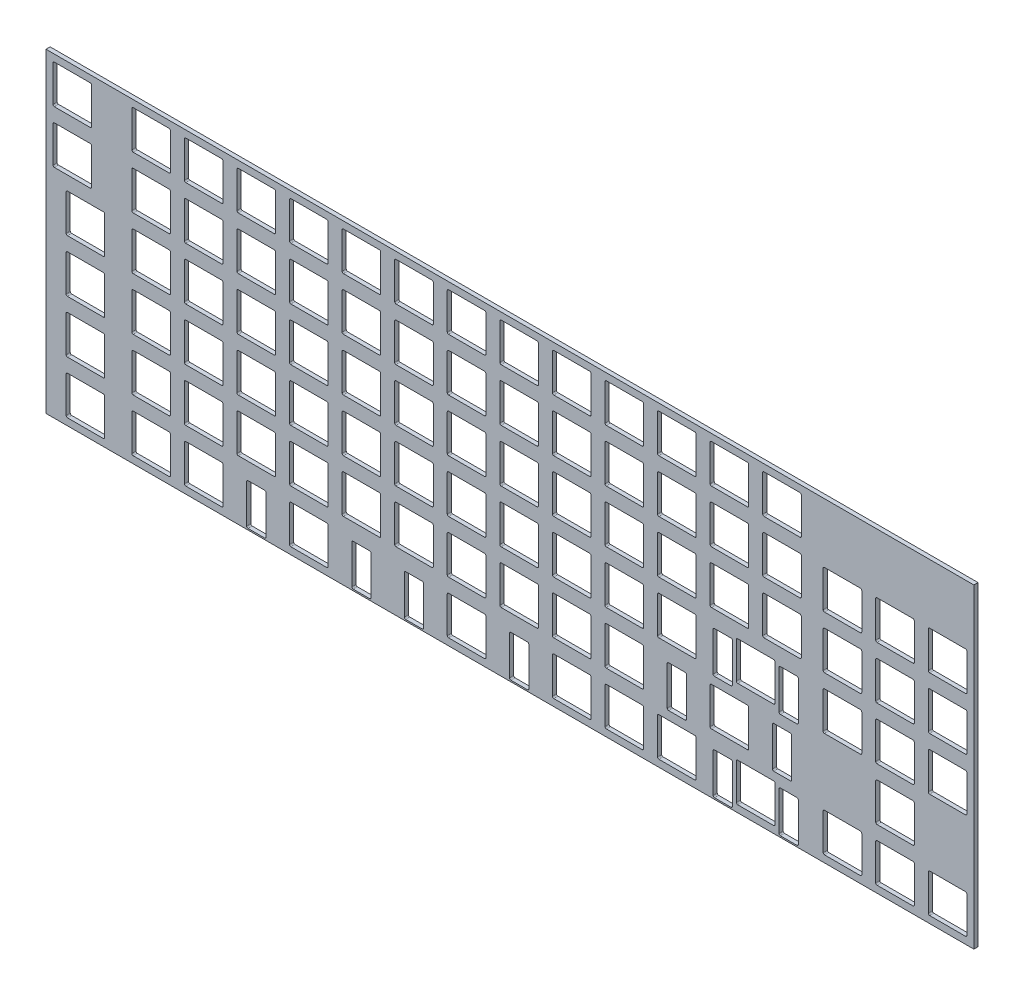
SolidWorks part; units mm, degrees
ref_plane "Front Plane" through (0, 0, 0) normal (0, 0, 1) x (1, 0, 0)
ref_plane "Top Plane" through (0, 0, 0) normal (0, 1, 0) x (1, 0, 0)
ref_plane "Right Plane" through (0, 0, 0) normal (1, 0, 0) x (0, 0, -1)
sketch "Model" plane through (0, 0, 0) normal (0, 0, 1) x (1, 0, 0)
  line L0 (3.025, -2.525) -> (16.025, -2.525)
  line L1 (3.025, -16.525) -> (16.025, -16.525)
  line L2 (2.525, -3.025) -> (2.525, -16.025)
  line L3 (16.525, -3.025) -> (16.525, -16.025)
  line L4 (31.6, -2.525) -> (44.6, -2.525)
  line L5 (31.6, -16.525) -> (44.6, -16.525)
  line L6 (31.1, -3.025) -> (31.1, -16.025)
  line L7 (45.1, -3.025) -> (45.1, -16.025)
  line L8 (50.65, -2.525) -> (63.65, -2.525)
  line L9 (50.65, -16.525) -> (63.65, -16.525)
  line L10 (50.15, -3.025) -> (50.15, -16.025)
  line L11 (64.15, -3.025) -> (64.15, -16.025)
  line L12 (69.7, -2.525) -> (82.7, -2.525)
  line L13 (69.7, -16.525) -> (82.7, -16.525)
  line L14 (69.2, -3.025) -> (69.2, -16.025)
  line L15 (83.2, -3.025) -> (83.2, -16.025)
  line L16 (88.75, -2.525) -> (101.75, -2.525)
  line L17 (88.75, -16.525) -> (101.75, -16.525)
  line L18 (88.25, -3.025) -> (88.25, -16.025)
  line L19 (102.25, -3.025) -> (102.25, -16.025)
  line L20 (107.8, -2.525) -> (120.8, -2.525)
  line L21 (107.8, -16.525) -> (120.8, -16.525)
  line L22 (107.3, -3.025) -> (107.3, -16.025)
  line L23 (121.3, -3.025) -> (121.3, -16.025)
  line L24 (126.85, -2.525) -> (139.85, -2.525)
  line L25 (126.85, -16.525) -> (139.85, -16.525)
  line L26 (126.35, -3.025) -> (126.35, -16.025)
  line L27 (140.35, -3.025) -> (140.35, -16.025)
  line L28 (145.9, -2.525) -> (158.9, -2.525)
  line L29 (145.9, -16.525) -> (158.9, -16.525)
  line L30 (145.4, -3.025) -> (145.4, -16.025)
  line L31 (159.4, -3.025) -> (159.4, -16.025)
  line L32 (164.95, -2.525) -> (177.95, -2.525)
  line L33 (164.95, -16.525) -> (177.95, -16.525)
  line L34 (164.45, -3.025) -> (164.45, -16.025)
  line L35 (178.45, -3.025) -> (178.45, -16.025)
  line L36 (184, -2.525) -> (197, -2.525)
  line L37 (184, -16.525) -> (197, -16.525)
  line L38 (183.5, -3.025) -> (183.5, -16.025)
  line L39 (197.5, -3.025) -> (197.5, -16.025)
  line L40 (203.05, -2.525) -> (216.05, -2.525)
  line L41 (203.05, -16.525) -> (216.05, -16.525)
  line L42 (202.55, -3.025) -> (202.55, -16.025)
  line L43 (216.55, -3.025) -> (216.55, -16.025)
  line L44 (222.1, -2.525) -> (235.1, -2.525)
  line L45 (222.1, -16.525) -> (235.1, -16.525)
  line L46 (221.6, -3.025) -> (221.6, -16.025)
  line L47 (235.6, -3.025) -> (235.6, -16.025)
  line L48 (241.15, -2.525) -> (254.15, -2.525)
  line L49 (241.15, -16.525) -> (254.15, -16.525)
  line L50 (240.65, -3.025) -> (240.65, -16.025)
  line L51 (254.65, -3.025) -> (254.65, -16.025)
  line L52 (260.2, -2.525) -> (273.2, -2.525)
  line L53 (260.2, -16.525) -> (273.2, -16.525)
  line L54 (259.7, -3.025) -> (259.7, -16.025)
  line L55 (273.7, -3.025) -> (273.7, -16.025)
  line L56 (3.025, -21.575) -> (16.025, -21.575)
  line L57 (3.025, -35.575) -> (16.025, -35.575)
  line L58 (2.525, -22.075) -> (2.525, -35.075)
  line L59 (16.525, -22.075) -> (16.525, -35.075)
  line L60 (31.6, -21.575) -> (44.6, -21.575)
  line L61 (31.6, -35.575) -> (44.6, -35.575)
  line L62 (31.1, -22.075) -> (31.1, -35.075)
  line L63 (45.1, -22.075) -> (45.1, -35.075)
  line L64 (50.65, -21.575) -> (63.65, -21.575)
  line L65 (50.65, -35.575) -> (63.65, -35.575)
  line L66 (50.15, -22.075) -> (50.15, -35.075)
  line L67 (64.15, -22.075) -> (64.15, -35.075)
  line L68 (69.7, -21.575) -> (82.7, -21.575)
  line L69 (69.7, -35.575) -> (82.7, -35.575)
  line L70 (69.2, -22.075) -> (69.2, -35.075)
  line L71 (83.2, -22.075) -> (83.2, -35.075)
  line L72 (88.75, -21.575) -> (101.75, -21.575)
  line L73 (88.75, -35.575) -> (101.75, -35.575)
  line L74 (88.25, -22.075) -> (88.25, -35.075)
  line L75 (102.25, -22.075) -> (102.25, -35.075)
  line L76 (107.8, -21.575) -> (120.8, -21.575)
  line L77 (107.8, -35.575) -> (120.8, -35.575)
  line L78 (107.3, -22.075) -> (107.3, -35.075)
  line L79 (121.3, -22.075) -> (121.3, -35.075)
  line L80 (126.85, -21.575) -> (139.85, -21.575)
  line L81 (126.85, -35.575) -> (139.85, -35.575)
  line L82 (126.35, -22.075) -> (126.35, -35.075)
  line L83 (140.35, -22.075) -> (140.35, -35.075)
  line L84 (145.9, -21.575) -> (158.9, -21.575)
  line L85 (145.9, -35.575) -> (158.9, -35.575)
  line L86 (145.4, -22.075) -> (145.4, -35.075)
  line L87 (159.4, -22.075) -> (159.4, -35.075)
  line L88 (164.95, -21.575) -> (177.95, -21.575)
  line L89 (164.95, -35.575) -> (177.95, -35.575)
  line L90 (164.45, -22.075) -> (164.45, -35.075)
  line L91 (178.45, -22.075) -> (178.45, -35.075)
  line L92 (184, -21.575) -> (197, -21.575)
  line L93 (184, -35.575) -> (197, -35.575)
  line L94 (183.5, -22.075) -> (183.5, -35.075)
  line L95 (197.5, -22.075) -> (197.5, -35.075)
  line L96 (203.05, -21.575) -> (216.05, -21.575)
  line L97 (203.05, -35.575) -> (216.05, -35.575)
  line L98 (202.55, -22.075) -> (202.55, -35.075)
  line L99 (216.55, -22.075) -> (216.55, -35.075)
  line L100 (222.1, -21.575) -> (235.1, -21.575)
  line L101 (222.1, -35.575) -> (235.1, -35.575)
  line L102 (221.6, -22.075) -> (221.6, -35.075)
  line L103 (235.6, -22.075) -> (235.6, -35.075)
  line L104 (241.15, -21.575) -> (254.15, -21.575)
  line L105 (241.15, -35.575) -> (254.15, -35.575)
  line L106 (240.65, -22.075) -> (240.65, -35.075)
  line L107 (254.65, -22.075) -> (254.65, -35.075)
  line L108 (260.2, -21.575) -> (273.2, -21.575)
  line L109 (260.2, -35.575) -> (273.2, -35.575)
  line L110 (259.7, -22.075) -> (259.7, -35.075)
  line L111 (273.7, -22.075) -> (273.7, -35.075)
  line L112 (282.1075, -21.575) -> (295.1075, -21.575)
  line L113 (282.1075, -35.575) -> (295.1075, -35.575)
  line L114 (281.6075, -22.075) -> (281.6075, -35.075)
  line L115 (295.6075, -22.075) -> (295.6075, -35.075)
  line L116 (301.1575, -21.575) -> (314.1575, -21.575)
  line L117 (301.1575, -35.575) -> (314.1575, -35.575)
  line L118 (300.6575, -22.075) -> (300.6575, -35.075)
  line L119 (314.6575, -22.075) -> (314.6575, -35.075)
  line L120 (320.2075, -21.575) -> (333.2075, -21.575)
  line L121 (320.2075, -35.575) -> (333.2075, -35.575)
  line L122 (319.7075, -22.075) -> (319.7075, -35.075)
  line L123 (333.7075, -22.075) -> (333.7075, -35.075)
  line L124 (7.7875, -40.625) -> (20.7875, -40.625)
  line L125 (7.7875, -54.625) -> (20.7875, -54.625)
  line L126 (7.2875, -41.125) -> (7.2875, -54.125)
  line L127 (21.2875, -41.125) -> (21.2875, -54.125)
  line L128 (31.6, -40.625) -> (44.6, -40.625)
  line L129 (31.6, -54.625) -> (44.6, -54.625)
  line L130 (31.1, -41.125) -> (31.1, -54.125)
  line L131 (45.1, -41.125) -> (45.1, -54.125)
  line L132 (50.65, -40.625) -> (63.65, -40.625)
  line L133 (50.65, -54.625) -> (63.65, -54.625)
  line L134 (50.15, -41.125) -> (50.15, -54.125)
  line L135 (64.15, -41.125) -> (64.15, -54.125)
  line L136 (69.7, -40.625) -> (82.7, -40.625)
  line L137 (69.7, -54.625) -> (82.7, -54.625)
  line L138 (69.2, -41.125) -> (69.2, -54.125)
  line L139 (83.2, -41.125) -> (83.2, -54.125)
  line L140 (88.75, -40.625) -> (101.75, -40.625)
  line L141 (88.75, -54.625) -> (101.75, -54.625)
  line L142 (88.25, -41.125) -> (88.25, -54.125)
  line L143 (102.25, -41.125) -> (102.25, -54.125)
  line L144 (107.8, -40.625) -> (120.8, -40.625)
  line L145 (107.8, -54.625) -> (120.8, -54.625)
  line L146 (107.3, -41.125) -> (107.3, -54.125)
  line L147 (121.3, -41.125) -> (121.3, -54.125)
  line L148 (126.85, -40.625) -> (139.85, -40.625)
  line L149 (126.85, -54.625) -> (139.85, -54.625)
  line L150 (126.35, -41.125) -> (126.35, -54.125)
  line L151 (140.35, -41.125) -> (140.35, -54.125)
  line L152 (145.9, -40.625) -> (158.9, -40.625)
  line L153 (145.9, -54.625) -> (158.9, -54.625)
  line L154 (145.4, -41.125) -> (145.4, -54.125)
  line L155 (159.4, -41.125) -> (159.4, -54.125)
  line L156 (164.95, -40.625) -> (177.95, -40.625)
  line L157 (164.95, -54.625) -> (177.95, -54.625)
  line L158 (164.45, -41.125) -> (164.45, -54.125)
  line L159 (178.45, -41.125) -> (178.45, -54.125)
  line L160 (184, -40.625) -> (197, -40.625)
  line L161 (184, -54.625) -> (197, -54.625)
  line L162 (183.5, -41.125) -> (183.5, -54.125)
  line L163 (197.5, -41.125) -> (197.5, -54.125)
  line L164 (203.05, -40.625) -> (216.05, -40.625)
  line L165 (203.05, -54.625) -> (216.05, -54.625)
  line L166 (202.55, -41.125) -> (202.55, -54.125)
  line L167 (216.55, -41.125) -> (216.55, -54.125)
  line L168 (222.1, -40.625) -> (235.1, -40.625)
  line L169 (222.1, -54.625) -> (235.1, -54.625)
  line L170 (221.6, -41.125) -> (221.6, -54.125)
  line L171 (235.6, -41.125) -> (235.6, -54.125)
  line L172 (241.15, -40.625) -> (254.15, -40.625)
  line L173 (241.15, -54.625) -> (254.15, -54.625)
  line L174 (240.65, -41.125) -> (240.65, -54.125)
  line L175 (254.65, -41.125) -> (254.65, -54.125)
  line L176 (260.2, -40.625) -> (273.2, -40.625)
  line L177 (260.2, -54.625) -> (273.2, -54.625)
  line L178 (259.7, -41.125) -> (259.7, -54.125)
  line L179 (273.7, -41.125) -> (273.7, -54.125)
  line L180 (282.1075, -40.625) -> (295.1075, -40.625)
  line L181 (282.1075, -54.625) -> (295.1075, -54.625)
  line L182 (281.6075, -41.125) -> (281.6075, -54.125)
  line L183 (295.6075, -41.125) -> (295.6075, -54.125)
  line L184 (301.1575, -40.625) -> (314.1575, -40.625)
  line L185 (301.1575, -54.625) -> (314.1575, -54.625)
  line L186 (300.6575, -41.125) -> (300.6575, -54.125)
  line L187 (314.6575, -41.125) -> (314.6575, -54.125)
  line L188 (320.2075, -40.625) -> (333.2075, -40.625)
  line L189 (320.2075, -54.625) -> (333.2075, -54.625)
  line L190 (319.7075, -41.125) -> (319.7075, -54.125)
  line L191 (333.7075, -41.125) -> (333.7075, -54.125)
  line L192 (7.7875, -59.675) -> (20.7875, -59.675)
  line L193 (7.7875, -73.675) -> (20.7875, -73.675)
  line L194 (7.2875, -60.175) -> (7.2875, -73.175)
  line L195 (21.2875, -60.175) -> (21.2875, -73.175)
  line L196 (31.6, -59.675) -> (44.6, -59.675)
  line L197 (31.6, -73.675) -> (44.6, -73.675)
  line L198 (31.1, -60.175) -> (31.1, -73.175)
  line L199 (45.1, -60.175) -> (45.1, -73.175)
  line L200 (50.65, -59.675) -> (63.65, -59.675)
  line L201 (50.65, -73.675) -> (63.65, -73.675)
  line L202 (50.15, -60.175) -> (50.15, -73.175)
  line L203 (64.15, -60.175) -> (64.15, -73.175)
  line L204 (69.7, -59.675) -> (82.7, -59.675)
  line L205 (69.7, -73.675) -> (82.7, -73.675)
  line L206 (69.2, -60.175) -> (69.2, -73.175)
  line L207 (83.2, -60.175) -> (83.2, -73.175)
  line L208 (88.75, -59.675) -> (101.75, -59.675)
  line L209 (88.75, -73.675) -> (101.75, -73.675)
  line L210 (88.25, -60.175) -> (88.25, -73.175)
  line L211 (102.25, -60.175) -> (102.25, -73.175)
  line L212 (107.8, -59.675) -> (120.8, -59.675)
  line L213 (107.8, -73.675) -> (120.8, -73.675)
  line L214 (107.3, -60.175) -> (107.3, -73.175)
  line L215 (121.3, -60.175) -> (121.3, -73.175)
  line L216 (126.85, -59.675) -> (139.85, -59.675)
  line L217 (126.85, -73.675) -> (139.85, -73.675)
  line L218 (126.35, -60.175) -> (126.35, -73.175)
  line L219 (140.35, -60.175) -> (140.35, -73.175)
  line L220 (145.9, -59.675) -> (158.9, -59.675)
  line L221 (145.9, -73.675) -> (158.9, -73.675)
  line L222 (145.4, -60.175) -> (145.4, -73.175)
  line L223 (159.4, -60.175) -> (159.4, -73.175)
  line L224 (164.95, -59.675) -> (177.95, -59.675)
  line L225 (164.95, -73.675) -> (177.95, -73.675)
  line L226 (164.45, -60.175) -> (164.45, -73.175)
  line L227 (178.45, -60.175) -> (178.45, -73.175)
  line L228 (184, -59.675) -> (197, -59.675)
  line L229 (184, -73.675) -> (197, -73.675)
  line L230 (183.5, -60.175) -> (183.5, -73.175)
  line L231 (197.5, -60.175) -> (197.5, -73.175)
  line L232 (203.05, -59.675) -> (216.05, -59.675)
  line L233 (203.05, -73.675) -> (216.05, -73.675)
  line L234 (202.55, -60.175) -> (202.55, -73.175)
  line L235 (216.55, -60.175) -> (216.55, -73.175)
  line L236 (222.1, -59.675) -> (235.1, -59.675)
  line L237 (222.1, -73.675) -> (235.1, -73.675)
  line L238 (221.6, -60.175) -> (221.6, -73.175)
  line L239 (235.6, -60.175) -> (235.6, -73.175)
  line L240 (250.675, -59.675) -> (263.675, -59.675)
  line L241 (250.675, -73.675) -> (263.675, -73.675)
  line L242 (250.175, -60.175) -> (250.175, -73.175)
  line L243 (264.175, -60.175) -> (264.175, -73.175)
  line L244 (242.237, -60.675) -> (248.237, -60.675)
  line L245 (242.237, -75.675) -> (248.237, -75.675)
  line L246 (241.737, -61.175) -> (241.737, -75.175)
  line L247 (248.737, -61.175) -> (248.737, -75.175)
  line L248 (266.113, -60.675) -> (272.113, -60.675)
  line L249 (266.113, -75.675) -> (272.113, -75.675)
  line L250 (265.613, -61.175) -> (265.613, -75.175)
  line L251 (272.613, -61.175) -> (272.613, -75.175)
  line L252 (282.1075, -59.675) -> (295.1075, -59.675)
  line L253 (282.1075, -73.675) -> (295.1075, -73.675)
  line L254 (281.6075, -60.175) -> (281.6075, -73.175)
  line L255 (295.6075, -60.175) -> (295.6075, -73.175)
  line L256 (301.1575, -59.675) -> (314.1575, -59.675)
  line L257 (301.1575, -73.675) -> (314.1575, -73.675)
  line L258 (300.6575, -60.175) -> (300.6575, -73.175)
  line L259 (314.6575, -60.175) -> (314.6575, -73.175)
  line L260 (320.2075, -59.675) -> (333.2075, -59.675)
  line L261 (320.2075, -73.675) -> (333.2075, -73.675)
  line L262 (319.7075, -60.175) -> (319.7075, -73.175)
  line L263 (333.7075, -60.175) -> (333.7075, -73.175)
  line L264 (7.7875, -78.725) -> (20.7875, -78.725)
  line L265 (7.7875, -92.725) -> (20.7875, -92.725)
  line L266 (7.2875, -79.225) -> (7.2875, -92.225)
  line L267 (21.2875, -79.225) -> (21.2875, -92.225)
  line L268 (31.6, -78.725) -> (44.6, -78.725)
  line L269 (31.6, -92.725) -> (44.6, -92.725)
  line L270 (31.1, -79.225) -> (31.1, -92.225)
  line L271 (45.1, -79.225) -> (45.1, -92.225)
  line L272 (50.65, -78.725) -> (63.65, -78.725)
  line L273 (50.65, -92.725) -> (63.65, -92.725)
  line L274 (50.15, -79.225) -> (50.15, -92.225)
  line L275 (64.15, -79.225) -> (64.15, -92.225)
  line L276 (69.7, -78.725) -> (82.7, -78.725)
  line L277 (69.7, -92.725) -> (82.7, -92.725)
  line L278 (69.2, -79.225) -> (69.2, -92.225)
  line L279 (83.2, -79.225) -> (83.2, -92.225)
  line L280 (88.75, -78.725) -> (101.75, -78.725)
  line L281 (88.75, -92.725) -> (101.75, -92.725)
  line L282 (88.25, -79.225) -> (88.25, -92.225)
  line L283 (102.25, -79.225) -> (102.25, -92.225)
  line L284 (107.8, -78.725) -> (120.8, -78.725)
  line L285 (107.8, -92.725) -> (120.8, -92.725)
  line L286 (107.3, -79.225) -> (107.3, -92.225)
  line L287 (121.3, -79.225) -> (121.3, -92.225)
  line L288 (126.85, -78.725) -> (139.85, -78.725)
  line L289 (126.85, -92.725) -> (139.85, -92.725)
  line L290 (126.35, -79.225) -> (126.35, -92.225)
  line L291 (140.35, -79.225) -> (140.35, -92.225)
  line L292 (145.9, -78.725) -> (158.9, -78.725)
  line L293 (145.9, -92.725) -> (158.9, -92.725)
  line L294 (145.4, -79.225) -> (145.4, -92.225)
  line L295 (159.4, -79.225) -> (159.4, -92.225)
  line L296 (164.95, -78.725) -> (177.95, -78.725)
  line L297 (164.95, -92.725) -> (177.95, -92.725)
  line L298 (164.45, -79.225) -> (164.45, -92.225)
  line L299 (178.45, -79.225) -> (178.45, -92.225)
  line L300 (184, -78.725) -> (197, -78.725)
  line L301 (184, -92.725) -> (197, -92.725)
  line L302 (183.5, -79.225) -> (183.5, -92.225)
  line L303 (197.5, -79.225) -> (197.5, -92.225)
  line L304 (203.05, -78.725) -> (216.05, -78.725)
  line L305 (203.05, -92.725) -> (216.05, -92.725)
  line L306 (202.55, -79.225) -> (202.55, -92.225)
  line L307 (216.55, -79.225) -> (216.55, -92.225)
  line L308 (241.15, -78.725) -> (254.15, -78.725)
  line L309 (241.15, -92.725) -> (254.15, -92.725)
  line L310 (240.65, -79.225) -> (240.65, -92.225)
  line L311 (254.65, -79.225) -> (254.65, -92.225)
  line L312 (225.6, -79.725) -> (231.6, -79.725)
  line L313 (225.6, -94.725) -> (231.6, -94.725)
  line L314 (225.1, -80.225) -> (225.1, -94.225)
  line L315 (232.1, -80.225) -> (232.1, -94.225)
  line L316 (263.7, -79.725) -> (269.7, -79.725)
  line L317 (263.7, -94.725) -> (269.7, -94.725)
  line L318 (263.2, -80.225) -> (263.2, -94.225)
  line L319 (270.2, -80.225) -> (270.2, -94.225)
  line L320 (301.1575, -78.725) -> (314.1575, -78.725)
  line L321 (301.1575, -92.725) -> (314.1575, -92.725)
  line L322 (300.6575, -79.225) -> (300.6575, -92.225)
  line L323 (314.6575, -79.225) -> (314.6575, -92.225)
  line L324 (7.7875, -97.775) -> (20.7875, -97.775)
  line L325 (7.7875, -111.775) -> (20.7875, -111.775)
  line L326 (7.2875, -98.275) -> (7.2875, -111.275)
  line L327 (21.2875, -98.275) -> (21.2875, -111.275)
  line L328 (31.6, -97.775) -> (44.6, -97.775)
  line L329 (31.6, -111.775) -> (44.6, -111.775)
  line L330 (31.1, -98.275) -> (31.1, -111.275)
  line L331 (45.1, -98.275) -> (45.1, -111.275)
  line L332 (50.65, -97.775) -> (63.65, -97.775)
  line L333 (50.65, -111.775) -> (63.65, -111.775)
  line L334 (50.15, -98.275) -> (50.15, -111.275)
  line L335 (64.15, -98.275) -> (64.15, -111.275)
  line L336 (88.75, -97.775) -> (101.75, -97.775)
  line L337 (88.75, -111.775) -> (101.75, -111.775)
  line L338 (88.25, -98.275) -> (88.25, -111.275)
  line L339 (102.25, -98.275) -> (102.25, -111.275)
  line L340 (73.2, -98.775) -> (79.2, -98.775)
  line L341 (73.2, -113.775) -> (79.2, -113.775)
  line L342 (72.7, -99.275) -> (72.7, -113.275)
  line L343 (79.7, -99.275) -> (79.7, -113.275)
  line L344 (111.3, -98.775) -> (117.3, -98.775)
  line L345 (111.3, -113.775) -> (117.3, -113.775)
  line L346 (110.8, -99.275) -> (110.8, -113.275)
  line L347 (117.8, -99.275) -> (117.8, -113.275)
  line L348 (145.9, -97.775) -> (158.9, -97.775)
  line L349 (145.9, -111.775) -> (158.9, -111.775)
  line L350 (145.4, -98.275) -> (145.4, -111.275)
  line L351 (159.4, -98.275) -> (159.4, -111.275)
  line L352 (130.35, -98.775) -> (136.35, -98.775)
  line L353 (130.35, -113.775) -> (136.35, -113.775)
  line L354 (129.85, -99.275) -> (129.85, -113.275)
  line L355 (136.85, -99.275) -> (136.85, -113.275)
  line L356 (168.45, -98.775) -> (174.45, -98.775)
  line L357 (168.45, -113.775) -> (174.45, -113.775)
  line L358 (167.95, -99.275) -> (167.95, -113.275)
  line L359 (174.95, -99.275) -> (174.95, -113.275)
  line L360 (184, -97.775) -> (197, -97.775)
  line L361 (184, -111.775) -> (197, -111.775)
  line L362 (183.5, -98.275) -> (183.5, -111.275)
  line L363 (197.5, -98.275) -> (197.5, -111.275)
  line L364 (203.05, -97.775) -> (216.05, -97.775)
  line L365 (203.05, -111.775) -> (216.05, -111.775)
  line L366 (202.55, -98.275) -> (202.55, -111.275)
  line L367 (216.55, -98.275) -> (216.55, -111.275)
  line L368 (222.1, -97.775) -> (235.1, -97.775)
  line L369 (222.1, -111.775) -> (235.1, -111.775)
  line L370 (221.6, -98.275) -> (221.6, -111.275)
  line L371 (235.6, -98.275) -> (235.6, -111.275)
  line L372 (250.675, -97.775) -> (263.675, -97.775)
  line L373 (250.675, -111.775) -> (263.675, -111.775)
  line L374 (250.175, -98.275) -> (250.175, -111.275)
  line L375 (264.175, -98.275) -> (264.175, -111.275)
  line L376 (242.237, -98.775) -> (248.237, -98.775)
  line L377 (242.237, -113.775) -> (248.237, -113.775)
  line L378 (241.737, -99.275) -> (241.737, -113.275)
  line L379 (248.737, -99.275) -> (248.737, -113.275)
  line L380 (266.113, -98.775) -> (272.113, -98.775)
  line L381 (266.113, -113.775) -> (272.113, -113.775)
  line L382 (265.613, -99.275) -> (265.613, -113.275)
  line L383 (272.613, -99.275) -> (272.613, -113.275)
  line L384 (282.1075, -97.775) -> (295.1075, -97.775)
  line L385 (282.1075, -111.775) -> (295.1075, -111.775)
  line L386 (281.6075, -98.275) -> (281.6075, -111.275)
  line L387 (295.6075, -98.275) -> (295.6075, -111.275)
  line L388 (301.1575, -97.775) -> (314.1575, -97.775)
  line L389 (301.1575, -111.775) -> (314.1575, -111.775)
  line L390 (300.6575, -98.275) -> (300.6575, -111.275)
  line L391 (314.6575, -98.275) -> (314.6575, -111.275)
  line L392 (320.2075, -97.775) -> (333.2075, -97.775)
  line L393 (320.2075, -111.775) -> (333.2075, -111.775)
  line L394 (319.7075, -98.275) -> (319.7075, -111.275)
  line L395 (333.7075, -98.275) -> (333.7075, -111.275)
  line L396 (0, -114.3) -> (336.2325, -114.3)
  line L397 (0, 0) -> (336.2325, 0)
  line L398 (0, -114.3) -> (0, 0)
  line L399 (336.2325, -114.3) -> (336.2325, 0)
  arc A0 (3.025, -2.525) -> (2.525, -3.025) centre (3.025, -3.025) ccw
  arc A1 (16.525, -3.025) -> (16.025, -2.525) centre (16.025, -3.025) ccw
  arc A2 (2.525, -16.025) -> (3.025, -16.525) centre (3.025, -16.025) ccw
  arc A3 (16.025, -16.525) -> (16.525, -16.025) centre (16.025, -16.025) ccw
  arc A4 (31.6, -2.525) -> (31.1, -3.025) centre (31.6, -3.025) ccw
  arc A5 (45.1, -3.025) -> (44.6, -2.525) centre (44.6, -3.025) ccw
  arc A6 (31.1, -16.025) -> (31.6, -16.525) centre (31.6, -16.025) ccw
  arc A7 (44.6, -16.525) -> (45.1, -16.025) centre (44.6, -16.025) ccw
  arc A8 (50.65, -2.525) -> (50.15, -3.025) centre (50.65, -3.025) ccw
  arc A9 (64.15, -3.025) -> (63.65, -2.525) centre (63.65, -3.025) ccw
  arc A10 (50.15, -16.025) -> (50.65, -16.525) centre (50.65, -16.025) ccw
  arc A11 (63.65, -16.525) -> (64.15, -16.025) centre (63.65, -16.025) ccw
  arc A12 (69.7, -2.525) -> (69.2, -3.025) centre (69.7, -3.025) ccw
  arc A13 (83.2, -3.025) -> (82.7, -2.525) centre (82.7, -3.025) ccw
  arc A14 (69.2, -16.025) -> (69.7, -16.525) centre (69.7, -16.025) ccw
  arc A15 (82.7, -16.525) -> (83.2, -16.025) centre (82.7, -16.025) ccw
  arc A16 (88.75, -2.525) -> (88.25, -3.025) centre (88.75, -3.025) ccw
  arc A17 (102.25, -3.025) -> (101.75, -2.525) centre (101.75, -3.025) ccw
  arc A18 (88.25, -16.025) -> (88.75, -16.525) centre (88.75, -16.025) ccw
  arc A19 (101.75, -16.525) -> (102.25, -16.025) centre (101.75, -16.025) ccw
  arc A20 (107.8, -2.525) -> (107.3, -3.025) centre (107.8, -3.025) ccw
  arc A21 (121.3, -3.025) -> (120.8, -2.525) centre (120.8, -3.025) ccw
  arc A22 (107.3, -16.025) -> (107.8, -16.525) centre (107.8, -16.025) ccw
  arc A23 (120.8, -16.525) -> (121.3, -16.025) centre (120.8, -16.025) ccw
  arc A24 (126.85, -2.525) -> (126.35, -3.025) centre (126.85, -3.025) ccw
  arc A25 (140.35, -3.025) -> (139.85, -2.525) centre (139.85, -3.025) ccw
  arc A26 (126.35, -16.025) -> (126.85, -16.525) centre (126.85, -16.025) ccw
  arc A27 (139.85, -16.525) -> (140.35, -16.025) centre (139.85, -16.025) ccw
  arc A28 (145.9, -2.525) -> (145.4, -3.025) centre (145.9, -3.025) ccw
  arc A29 (159.4, -3.025) -> (158.9, -2.525) centre (158.9, -3.025) ccw
  arc A30 (145.4, -16.025) -> (145.9, -16.525) centre (145.9, -16.025) ccw
  arc A31 (158.9, -16.525) -> (159.4, -16.025) centre (158.9, -16.025) ccw
  arc A32 (164.95, -2.525) -> (164.45, -3.025) centre (164.95, -3.025) ccw
  arc A33 (178.45, -3.025) -> (177.95, -2.525) centre (177.95, -3.025) ccw
  arc A34 (164.45, -16.025) -> (164.95, -16.525) centre (164.95, -16.025) ccw
  arc A35 (177.95, -16.525) -> (178.45, -16.025) centre (177.95, -16.025) ccw
  arc A36 (184, -2.525) -> (183.5, -3.025) centre (184, -3.025) ccw
  arc A37 (197.5, -3.025) -> (197, -2.525) centre (197, -3.025) ccw
  arc A38 (183.5, -16.025) -> (184, -16.525) centre (184, -16.025) ccw
  arc A39 (197, -16.525) -> (197.5, -16.025) centre (197, -16.025) ccw
  arc A40 (203.05, -2.525) -> (202.55, -3.025) centre (203.05, -3.025) ccw
  arc A41 (216.55, -3.025) -> (216.05, -2.525) centre (216.05, -3.025) ccw
  arc A42 (202.55, -16.025) -> (203.05, -16.525) centre (203.05, -16.025) ccw
  arc A43 (216.05, -16.525) -> (216.55, -16.025) centre (216.05, -16.025) ccw
  arc A44 (222.1, -2.525) -> (221.6, -3.025) centre (222.1, -3.025) ccw
  arc A45 (235.6, -3.025) -> (235.1, -2.525) centre (235.1, -3.025) ccw
  arc A46 (221.6, -16.025) -> (222.1, -16.525) centre (222.1, -16.025) ccw
  arc A47 (235.1, -16.525) -> (235.6, -16.025) centre (235.1, -16.025) ccw
  arc A48 (241.15, -2.525) -> (240.65, -3.025) centre (241.15, -3.025) ccw
  arc A49 (254.65, -3.025) -> (254.15, -2.525) centre (254.15, -3.025) ccw
  arc A50 (240.65, -16.025) -> (241.15, -16.525) centre (241.15, -16.025) ccw
  arc A51 (254.15, -16.525) -> (254.65, -16.025) centre (254.15, -16.025) ccw
  arc A52 (260.2, -2.525) -> (259.7, -3.025) centre (260.2, -3.025) ccw
  arc A53 (273.7, -3.025) -> (273.2, -2.525) centre (273.2, -3.025) ccw
  arc A54 (259.7, -16.025) -> (260.2, -16.525) centre (260.2, -16.025) ccw
  arc A55 (273.2, -16.525) -> (273.7, -16.025) centre (273.2, -16.025) ccw
  arc A56 (3.025, -21.575) -> (2.525, -22.075) centre (3.025, -22.075) ccw
  arc A57 (16.525, -22.075) -> (16.025, -21.575) centre (16.025, -22.075) ccw
  arc A58 (2.525, -35.075) -> (3.025, -35.575) centre (3.025, -35.075) ccw
  arc A59 (16.025, -35.575) -> (16.525, -35.075) centre (16.025, -35.075) ccw
  arc A60 (31.6, -21.575) -> (31.1, -22.075) centre (31.6, -22.075) ccw
  arc A61 (45.1, -22.075) -> (44.6, -21.575) centre (44.6, -22.075) ccw
  arc A62 (31.1, -35.075) -> (31.6, -35.575) centre (31.6, -35.075) ccw
  arc A63 (44.6, -35.575) -> (45.1, -35.075) centre (44.6, -35.075) ccw
  arc A64 (50.65, -21.575) -> (50.15, -22.075) centre (50.65, -22.075) ccw
  arc A65 (64.15, -22.075) -> (63.65, -21.575) centre (63.65, -22.075) ccw
  arc A66 (50.15, -35.075) -> (50.65, -35.575) centre (50.65, -35.075) ccw
  arc A67 (63.65, -35.575) -> (64.15, -35.075) centre (63.65, -35.075) ccw
  arc A68 (69.7, -21.575) -> (69.2, -22.075) centre (69.7, -22.075) ccw
  arc A69 (83.2, -22.075) -> (82.7, -21.575) centre (82.7, -22.075) ccw
  arc A70 (69.2, -35.075) -> (69.7, -35.575) centre (69.7, -35.075) ccw
  arc A71 (82.7, -35.575) -> (83.2, -35.075) centre (82.7, -35.075) ccw
  arc A72 (88.75, -21.575) -> (88.25, -22.075) centre (88.75, -22.075) ccw
  arc A73 (102.25, -22.075) -> (101.75, -21.575) centre (101.75, -22.075) ccw
  arc A74 (88.25, -35.075) -> (88.75, -35.575) centre (88.75, -35.075) ccw
  arc A75 (101.75, -35.575) -> (102.25, -35.075) centre (101.75, -35.075) ccw
  arc A76 (107.8, -21.575) -> (107.3, -22.075) centre (107.8, -22.075) ccw
  arc A77 (121.3, -22.075) -> (120.8, -21.575) centre (120.8, -22.075) ccw
  arc A78 (107.3, -35.075) -> (107.8, -35.575) centre (107.8, -35.075) ccw
  arc A79 (120.8, -35.575) -> (121.3, -35.075) centre (120.8, -35.075) ccw
  arc A80 (126.85, -21.575) -> (126.35, -22.075) centre (126.85, -22.075) ccw
  arc A81 (140.35, -22.075) -> (139.85, -21.575) centre (139.85, -22.075) ccw
  arc A82 (126.35, -35.075) -> (126.85, -35.575) centre (126.85, -35.075) ccw
  arc A83 (139.85, -35.575) -> (140.35, -35.075) centre (139.85, -35.075) ccw
  arc A84 (145.9, -21.575) -> (145.4, -22.075) centre (145.9, -22.075) ccw
  arc A85 (159.4, -22.075) -> (158.9, -21.575) centre (158.9, -22.075) ccw
  arc A86 (145.4, -35.075) -> (145.9, -35.575) centre (145.9, -35.075) ccw
  arc A87 (158.9, -35.575) -> (159.4, -35.075) centre (158.9, -35.075) ccw
  arc A88 (164.95, -21.575) -> (164.45, -22.075) centre (164.95, -22.075) ccw
  arc A89 (178.45, -22.075) -> (177.95, -21.575) centre (177.95, -22.075) ccw
  arc A90 (164.45, -35.075) -> (164.95, -35.575) centre (164.95, -35.075) ccw
  arc A91 (177.95, -35.575) -> (178.45, -35.075) centre (177.95, -35.075) ccw
  arc A92 (184, -21.575) -> (183.5, -22.075) centre (184, -22.075) ccw
  arc A93 (197.5, -22.075) -> (197, -21.575) centre (197, -22.075) ccw
  arc A94 (183.5, -35.075) -> (184, -35.575) centre (184, -35.075) ccw
  arc A95 (197, -35.575) -> (197.5, -35.075) centre (197, -35.075) ccw
  arc A96 (203.05, -21.575) -> (202.55, -22.075) centre (203.05, -22.075) ccw
  arc A97 (216.55, -22.075) -> (216.05, -21.575) centre (216.05, -22.075) ccw
  arc A98 (202.55, -35.075) -> (203.05, -35.575) centre (203.05, -35.075) ccw
  arc A99 (216.05, -35.575) -> (216.55, -35.075) centre (216.05, -35.075) ccw
  arc A100 (222.1, -21.575) -> (221.6, -22.075) centre (222.1, -22.075) ccw
  arc A101 (235.6, -22.075) -> (235.1, -21.575) centre (235.1, -22.075) ccw
  arc A102 (221.6, -35.075) -> (222.1, -35.575) centre (222.1, -35.075) ccw
  arc A103 (235.1, -35.575) -> (235.6, -35.075) centre (235.1, -35.075) ccw
  arc A104 (241.15, -21.575) -> (240.65, -22.075) centre (241.15, -22.075) ccw
  arc A105 (254.65, -22.075) -> (254.15, -21.575) centre (254.15, -22.075) ccw
  arc A106 (240.65, -35.075) -> (241.15, -35.575) centre (241.15, -35.075) ccw
  arc A107 (254.15, -35.575) -> (254.65, -35.075) centre (254.15, -35.075) ccw
  arc A108 (260.2, -21.575) -> (259.7, -22.075) centre (260.2, -22.075) ccw
  arc A109 (273.7, -22.075) -> (273.2, -21.575) centre (273.2, -22.075) ccw
  arc A110 (259.7, -35.075) -> (260.2, -35.575) centre (260.2, -35.075) ccw
  arc A111 (273.2, -35.575) -> (273.7, -35.075) centre (273.2, -35.075) ccw
  arc A112 (282.1075, -21.575) -> (281.6075, -22.075) centre (282.1075, -22.075) ccw
  arc A113 (295.6075, -22.075) -> (295.1075, -21.575) centre (295.1075, -22.075) ccw
  arc A114 (281.6075, -35.075) -> (282.1075, -35.575) centre (282.1075, -35.075) ccw
  arc A115 (295.1075, -35.575) -> (295.6075, -35.075) centre (295.1075, -35.075) ccw
  arc A116 (301.1575, -21.575) -> (300.6575, -22.075) centre (301.1575, -22.075) ccw
  arc A117 (314.6575, -22.075) -> (314.1575, -21.575) centre (314.1575, -22.075) ccw
  arc A118 (300.6575, -35.075) -> (301.1575, -35.575) centre (301.1575, -35.075) ccw
  arc A119 (314.1575, -35.575) -> (314.6575, -35.075) centre (314.1575, -35.075) ccw
  arc A120 (320.2075, -21.575) -> (319.7075, -22.075) centre (320.2075, -22.075) ccw
  arc A121 (333.7075, -22.075) -> (333.2075, -21.575) centre (333.2075, -22.075) ccw
  arc A122 (319.7075, -35.075) -> (320.2075, -35.575) centre (320.2075, -35.075) ccw
  arc A123 (333.2075, -35.575) -> (333.7075, -35.075) centre (333.2075, -35.075) ccw
  arc A124 (7.7875, -40.625) -> (7.2875, -41.125) centre (7.7875, -41.125) ccw
  arc A125 (21.2875, -41.125) -> (20.7875, -40.625) centre (20.7875, -41.125) ccw
  arc A126 (7.2875, -54.125) -> (7.7875, -54.625) centre (7.7875, -54.125) ccw
  arc A127 (20.7875, -54.625) -> (21.2875, -54.125) centre (20.7875, -54.125) ccw
  arc A128 (31.6, -40.625) -> (31.1, -41.125) centre (31.6, -41.125) ccw
  arc A129 (45.1, -41.125) -> (44.6, -40.625) centre (44.6, -41.125) ccw
  arc A130 (31.1, -54.125) -> (31.6, -54.625) centre (31.6, -54.125) ccw
  arc A131 (44.6, -54.625) -> (45.1, -54.125) centre (44.6, -54.125) ccw
  arc A132 (50.65, -40.625) -> (50.15, -41.125) centre (50.65, -41.125) ccw
  arc A133 (64.15, -41.125) -> (63.65, -40.625) centre (63.65, -41.125) ccw
  arc A134 (50.15, -54.125) -> (50.65, -54.625) centre (50.65, -54.125) ccw
  arc A135 (63.65, -54.625) -> (64.15, -54.125) centre (63.65, -54.125) ccw
  arc A136 (69.7, -40.625) -> (69.2, -41.125) centre (69.7, -41.125) ccw
  arc A137 (83.2, -41.125) -> (82.7, -40.625) centre (82.7, -41.125) ccw
  arc A138 (69.2, -54.125) -> (69.7, -54.625) centre (69.7, -54.125) ccw
  arc A139 (82.7, -54.625) -> (83.2, -54.125) centre (82.7, -54.125) ccw
  arc A140 (88.75, -40.625) -> (88.25, -41.125) centre (88.75, -41.125) ccw
  arc A141 (102.25, -41.125) -> (101.75, -40.625) centre (101.75, -41.125) ccw
  arc A142 (88.25, -54.125) -> (88.75, -54.625) centre (88.75, -54.125) ccw
  arc A143 (101.75, -54.625) -> (102.25, -54.125) centre (101.75, -54.125) ccw
  arc A144 (107.8, -40.625) -> (107.3, -41.125) centre (107.8, -41.125) ccw
  arc A145 (121.3, -41.125) -> (120.8, -40.625) centre (120.8, -41.125) ccw
  arc A146 (107.3, -54.125) -> (107.8, -54.625) centre (107.8, -54.125) ccw
  arc A147 (120.8, -54.625) -> (121.3, -54.125) centre (120.8, -54.125) ccw
  arc A148 (126.85, -40.625) -> (126.35, -41.125) centre (126.85, -41.125) ccw
  arc A149 (140.35, -41.125) -> (139.85, -40.625) centre (139.85, -41.125) ccw
  arc A150 (126.35, -54.125) -> (126.85, -54.625) centre (126.85, -54.125) ccw
  arc A151 (139.85, -54.625) -> (140.35, -54.125) centre (139.85, -54.125) ccw
  arc A152 (145.9, -40.625) -> (145.4, -41.125) centre (145.9, -41.125) ccw
  arc A153 (159.4, -41.125) -> (158.9, -40.625) centre (158.9, -41.125) ccw
  arc A154 (145.4, -54.125) -> (145.9, -54.625) centre (145.9, -54.125) ccw
  arc A155 (158.9, -54.625) -> (159.4, -54.125) centre (158.9, -54.125) ccw
  arc A156 (164.95, -40.625) -> (164.45, -41.125) centre (164.95, -41.125) ccw
  arc A157 (178.45, -41.125) -> (177.95, -40.625) centre (177.95, -41.125) ccw
  arc A158 (164.45, -54.125) -> (164.95, -54.625) centre (164.95, -54.125) ccw
  arc A159 (177.95, -54.625) -> (178.45, -54.125) centre (177.95, -54.125) ccw
  arc A160 (184, -40.625) -> (183.5, -41.125) centre (184, -41.125) ccw
  arc A161 (197.5, -41.125) -> (197, -40.625) centre (197, -41.125) ccw
  arc A162 (183.5, -54.125) -> (184, -54.625) centre (184, -54.125) ccw
  arc A163 (197, -54.625) -> (197.5, -54.125) centre (197, -54.125) ccw
  arc A164 (203.05, -40.625) -> (202.55, -41.125) centre (203.05, -41.125) ccw
  arc A165 (216.55, -41.125) -> (216.05, -40.625) centre (216.05, -41.125) ccw
  arc A166 (202.55, -54.125) -> (203.05, -54.625) centre (203.05, -54.125) ccw
  arc A167 (216.05, -54.625) -> (216.55, -54.125) centre (216.05, -54.125) ccw
  arc A168 (222.1, -40.625) -> (221.6, -41.125) centre (222.1, -41.125) ccw
  arc A169 (235.6, -41.125) -> (235.1, -40.625) centre (235.1, -41.125) ccw
  arc A170 (221.6, -54.125) -> (222.1, -54.625) centre (222.1, -54.125) ccw
  arc A171 (235.1, -54.625) -> (235.6, -54.125) centre (235.1, -54.125) ccw
  arc A172 (241.15, -40.625) -> (240.65, -41.125) centre (241.15, -41.125) ccw
  arc A173 (254.65, -41.125) -> (254.15, -40.625) centre (254.15, -41.125) ccw
  arc A174 (240.65, -54.125) -> (241.15, -54.625) centre (241.15, -54.125) ccw
  arc A175 (254.15, -54.625) -> (254.65, -54.125) centre (254.15, -54.125) ccw
  arc A176 (260.2, -40.625) -> (259.7, -41.125) centre (260.2, -41.125) ccw
  arc A177 (273.7, -41.125) -> (273.2, -40.625) centre (273.2, -41.125) ccw
  arc A178 (259.7, -54.125) -> (260.2, -54.625) centre (260.2, -54.125) ccw
  arc A179 (273.2, -54.625) -> (273.7, -54.125) centre (273.2, -54.125) ccw
  arc A180 (282.1075, -40.625) -> (281.6075, -41.125) centre (282.1075, -41.125) ccw
  arc A181 (295.6075, -41.125) -> (295.1075, -40.625) centre (295.1075, -41.125) ccw
  arc A182 (281.6075, -54.125) -> (282.1075, -54.625) centre (282.1075, -54.125) ccw
  arc A183 (295.1075, -54.625) -> (295.6075, -54.125) centre (295.1075, -54.125) ccw
  arc A184 (301.1575, -40.625) -> (300.6575, -41.125) centre (301.1575, -41.125) ccw
  arc A185 (314.6575, -41.125) -> (314.1575, -40.625) centre (314.1575, -41.125) ccw
  arc A186 (300.6575, -54.125) -> (301.1575, -54.625) centre (301.1575, -54.125) ccw
  arc A187 (314.1575, -54.625) -> (314.6575, -54.125) centre (314.1575, -54.125) ccw
  arc A188 (320.2075, -40.625) -> (319.7075, -41.125) centre (320.2075, -41.125) ccw
  arc A189 (333.7075, -41.125) -> (333.2075, -40.625) centre (333.2075, -41.125) ccw
  arc A190 (319.7075, -54.125) -> (320.2075, -54.625) centre (320.2075, -54.125) ccw
  arc A191 (333.2075, -54.625) -> (333.7075, -54.125) centre (333.2075, -54.125) ccw
  arc A192 (7.7875, -59.675) -> (7.2875, -60.175) centre (7.7875, -60.175) ccw
  arc A193 (21.2875, -60.175) -> (20.7875, -59.675) centre (20.7875, -60.175) ccw
  arc A194 (7.2875, -73.175) -> (7.7875, -73.675) centre (7.7875, -73.175) ccw
  arc A195 (20.7875, -73.675) -> (21.2875, -73.175) centre (20.7875, -73.175) ccw
  arc A196 (31.6, -59.675) -> (31.1, -60.175) centre (31.6, -60.175) ccw
  arc A197 (45.1, -60.175) -> (44.6, -59.675) centre (44.6, -60.175) ccw
  arc A198 (31.1, -73.175) -> (31.6, -73.675) centre (31.6, -73.175) ccw
  arc A199 (44.6, -73.675) -> (45.1, -73.175) centre (44.6, -73.175) ccw
  arc A200 (50.65, -59.675) -> (50.15, -60.175) centre (50.65, -60.175) ccw
  arc A201 (64.15, -60.175) -> (63.65, -59.675) centre (63.65, -60.175) ccw
  arc A202 (50.15, -73.175) -> (50.65, -73.675) centre (50.65, -73.175) ccw
  arc A203 (63.65, -73.675) -> (64.15, -73.175) centre (63.65, -73.175) ccw
  arc A204 (69.7, -59.675) -> (69.2, -60.175) centre (69.7, -60.175) ccw
  arc A205 (83.2, -60.175) -> (82.7, -59.675) centre (82.7, -60.175) ccw
  arc A206 (69.2, -73.175) -> (69.7, -73.675) centre (69.7, -73.175) ccw
  arc A207 (82.7, -73.675) -> (83.2, -73.175) centre (82.7, -73.175) ccw
  arc A208 (88.75, -59.675) -> (88.25, -60.175) centre (88.75, -60.175) ccw
  arc A209 (102.25, -60.175) -> (101.75, -59.675) centre (101.75, -60.175) ccw
  arc A210 (88.25, -73.175) -> (88.75, -73.675) centre (88.75, -73.175) ccw
  arc A211 (101.75, -73.675) -> (102.25, -73.175) centre (101.75, -73.175) ccw
  arc A212 (107.8, -59.675) -> (107.3, -60.175) centre (107.8, -60.175) ccw
  arc A213 (121.3, -60.175) -> (120.8, -59.675) centre (120.8, -60.175) ccw
  arc A214 (107.3, -73.175) -> (107.8, -73.675) centre (107.8, -73.175) ccw
  arc A215 (120.8, -73.675) -> (121.3, -73.175) centre (120.8, -73.175) ccw
  arc A216 (126.85, -59.675) -> (126.35, -60.175) centre (126.85, -60.175) ccw
  arc A217 (140.35, -60.175) -> (139.85, -59.675) centre (139.85, -60.175) ccw
  arc A218 (126.35, -73.175) -> (126.85, -73.675) centre (126.85, -73.175) ccw
  arc A219 (139.85, -73.675) -> (140.35, -73.175) centre (139.85, -73.175) ccw
  arc A220 (145.9, -59.675) -> (145.4, -60.175) centre (145.9, -60.175) ccw
  arc A221 (159.4, -60.175) -> (158.9, -59.675) centre (158.9, -60.175) ccw
  arc A222 (145.4, -73.175) -> (145.9, -73.675) centre (145.9, -73.175) ccw
  arc A223 (158.9, -73.675) -> (159.4, -73.175) centre (158.9, -73.175) ccw
  arc A224 (164.95, -59.675) -> (164.45, -60.175) centre (164.95, -60.175) ccw
  arc A225 (178.45, -60.175) -> (177.95, -59.675) centre (177.95, -60.175) ccw
  arc A226 (164.45, -73.175) -> (164.95, -73.675) centre (164.95, -73.175) ccw
  arc A227 (177.95, -73.675) -> (178.45, -73.175) centre (177.95, -73.175) ccw
  arc A228 (184, -59.675) -> (183.5, -60.175) centre (184, -60.175) ccw
  arc A229 (197.5, -60.175) -> (197, -59.675) centre (197, -60.175) ccw
  arc A230 (183.5, -73.175) -> (184, -73.675) centre (184, -73.175) ccw
  arc A231 (197, -73.675) -> (197.5, -73.175) centre (197, -73.175) ccw
  arc A232 (203.05, -59.675) -> (202.55, -60.175) centre (203.05, -60.175) ccw
  arc A233 (216.55, -60.175) -> (216.05, -59.675) centre (216.05, -60.175) ccw
  arc A234 (202.55, -73.175) -> (203.05, -73.675) centre (203.05, -73.175) ccw
  arc A235 (216.05, -73.675) -> (216.55, -73.175) centre (216.05, -73.175) ccw
  arc A236 (222.1, -59.675) -> (221.6, -60.175) centre (222.1, -60.175) ccw
  arc A237 (235.6, -60.175) -> (235.1, -59.675) centre (235.1, -60.175) ccw
  arc A238 (221.6, -73.175) -> (222.1, -73.675) centre (222.1, -73.175) ccw
  arc A239 (235.1, -73.675) -> (235.6, -73.175) centre (235.1, -73.175) ccw
  arc A240 (250.675, -59.675) -> (250.175, -60.175) centre (250.675, -60.175) ccw
  arc A241 (264.175, -60.175) -> (263.675, -59.675) centre (263.675, -60.175) ccw
  arc A242 (250.175, -73.175) -> (250.675, -73.675) centre (250.675, -73.175) ccw
  arc A243 (263.675, -73.675) -> (264.175, -73.175) centre (263.675, -73.175) ccw
  arc A244 (242.237, -60.675) -> (241.737, -61.175) centre (242.237, -61.175) ccw
  arc A245 (248.737, -61.175) -> (248.237, -60.675) centre (248.237, -61.175) ccw
  arc A246 (241.737, -75.175) -> (242.237, -75.675) centre (242.237, -75.175) ccw
  arc A247 (248.237, -75.675) -> (248.737, -75.175) centre (248.237, -75.175) ccw
  arc A248 (266.113, -60.675) -> (265.613, -61.175) centre (266.113, -61.175) ccw
  arc A249 (272.613, -61.175) -> (272.113, -60.675) centre (272.113, -61.175) ccw
  arc A250 (265.613, -75.175) -> (266.113, -75.675) centre (266.113, -75.175) ccw
  arc A251 (272.113, -75.675) -> (272.613, -75.175) centre (272.113, -75.175) ccw
  arc A252 (282.1075, -59.675) -> (281.6075, -60.175) centre (282.1075, -60.175) ccw
  arc A253 (295.6075, -60.175) -> (295.1075, -59.675) centre (295.1075, -60.175) ccw
  arc A254 (281.6075, -73.175) -> (282.1075, -73.675) centre (282.1075, -73.175) ccw
  arc A255 (295.1075, -73.675) -> (295.6075, -73.175) centre (295.1075, -73.175) ccw
  arc A256 (301.1575, -59.675) -> (300.6575, -60.175) centre (301.1575, -60.175) ccw
  arc A257 (314.6575, -60.175) -> (314.1575, -59.675) centre (314.1575, -60.175) ccw
  arc A258 (300.6575, -73.175) -> (301.1575, -73.675) centre (301.1575, -73.175) ccw
  arc A259 (314.1575, -73.675) -> (314.6575, -73.175) centre (314.1575, -73.175) ccw
  arc A260 (320.2075, -59.675) -> (319.7075, -60.175) centre (320.2075, -60.175) ccw
  arc A261 (333.7075, -60.175) -> (333.2075, -59.675) centre (333.2075, -60.175) ccw
  arc A262 (319.7075, -73.175) -> (320.2075, -73.675) centre (320.2075, -73.175) ccw
  arc A263 (333.2075, -73.675) -> (333.7075, -73.175) centre (333.2075, -73.175) ccw
  arc A264 (7.7875, -78.725) -> (7.2875, -79.225) centre (7.7875, -79.225) ccw
  arc A265 (21.2875, -79.225) -> (20.7875, -78.725) centre (20.7875, -79.225) ccw
  arc A266 (7.2875, -92.225) -> (7.7875, -92.725) centre (7.7875, -92.225) ccw
  arc A267 (20.7875, -92.725) -> (21.2875, -92.225) centre (20.7875, -92.225) ccw
  arc A268 (31.6, -78.725) -> (31.1, -79.225) centre (31.6, -79.225) ccw
  arc A269 (45.1, -79.225) -> (44.6, -78.725) centre (44.6, -79.225) ccw
  arc A270 (31.1, -92.225) -> (31.6, -92.725) centre (31.6, -92.225) ccw
  arc A271 (44.6, -92.725) -> (45.1, -92.225) centre (44.6, -92.225) ccw
  arc A272 (50.65, -78.725) -> (50.15, -79.225) centre (50.65, -79.225) ccw
  arc A273 (64.15, -79.225) -> (63.65, -78.725) centre (63.65, -79.225) ccw
  arc A274 (50.15, -92.225) -> (50.65, -92.725) centre (50.65, -92.225) ccw
  arc A275 (63.65, -92.725) -> (64.15, -92.225) centre (63.65, -92.225) ccw
  arc A276 (69.7, -78.725) -> (69.2, -79.225) centre (69.7, -79.225) ccw
  arc A277 (83.2, -79.225) -> (82.7, -78.725) centre (82.7, -79.225) ccw
  arc A278 (69.2, -92.225) -> (69.7, -92.725) centre (69.7, -92.225) ccw
  arc A279 (82.7, -92.725) -> (83.2, -92.225) centre (82.7, -92.225) ccw
  arc A280 (88.75, -78.725) -> (88.25, -79.225) centre (88.75, -79.225) ccw
  arc A281 (102.25, -79.225) -> (101.75, -78.725) centre (101.75, -79.225) ccw
  arc A282 (88.25, -92.225) -> (88.75, -92.725) centre (88.75, -92.225) ccw
  arc A283 (101.75, -92.725) -> (102.25, -92.225) centre (101.75, -92.225) ccw
  arc A284 (107.8, -78.725) -> (107.3, -79.225) centre (107.8, -79.225) ccw
  arc A285 (121.3, -79.225) -> (120.8, -78.725) centre (120.8, -79.225) ccw
  arc A286 (107.3, -92.225) -> (107.8, -92.725) centre (107.8, -92.225) ccw
  arc A287 (120.8, -92.725) -> (121.3, -92.225) centre (120.8, -92.225) ccw
  arc A288 (126.85, -78.725) -> (126.35, -79.225) centre (126.85, -79.225) ccw
  arc A289 (140.35, -79.225) -> (139.85, -78.725) centre (139.85, -79.225) ccw
  arc A290 (126.35, -92.225) -> (126.85, -92.725) centre (126.85, -92.225) ccw
  arc A291 (139.85, -92.725) -> (140.35, -92.225) centre (139.85, -92.225) ccw
  arc A292 (145.9, -78.725) -> (145.4, -79.225) centre (145.9, -79.225) ccw
  arc A293 (159.4, -79.225) -> (158.9, -78.725) centre (158.9, -79.225) ccw
  arc A294 (145.4, -92.225) -> (145.9, -92.725) centre (145.9, -92.225) ccw
  arc A295 (158.9, -92.725) -> (159.4, -92.225) centre (158.9, -92.225) ccw
  arc A296 (164.95, -78.725) -> (164.45, -79.225) centre (164.95, -79.225) ccw
  arc A297 (178.45, -79.225) -> (177.95, -78.725) centre (177.95, -79.225) ccw
  arc A298 (164.45, -92.225) -> (164.95, -92.725) centre (164.95, -92.225) ccw
  arc A299 (177.95, -92.725) -> (178.45, -92.225) centre (177.95, -92.225) ccw
  arc A300 (184, -78.725) -> (183.5, -79.225) centre (184, -79.225) ccw
  arc A301 (197.5, -79.225) -> (197, -78.725) centre (197, -79.225) ccw
  arc A302 (183.5, -92.225) -> (184, -92.725) centre (184, -92.225) ccw
  arc A303 (197, -92.725) -> (197.5, -92.225) centre (197, -92.225) ccw
  arc A304 (203.05, -78.725) -> (202.55, -79.225) centre (203.05, -79.225) ccw
  arc A305 (216.55, -79.225) -> (216.05, -78.725) centre (216.05, -79.225) ccw
  arc A306 (202.55, -92.225) -> (203.05, -92.725) centre (203.05, -92.225) ccw
  arc A307 (216.05, -92.725) -> (216.55, -92.225) centre (216.05, -92.225) ccw
  arc A308 (241.15, -78.725) -> (240.65, -79.225) centre (241.15, -79.225) ccw
  arc A309 (254.65, -79.225) -> (254.15, -78.725) centre (254.15, -79.225) ccw
  arc A310 (240.65, -92.225) -> (241.15, -92.725) centre (241.15, -92.225) ccw
  arc A311 (254.15, -92.725) -> (254.65, -92.225) centre (254.15, -92.225) ccw
  arc A312 (225.6, -79.725) -> (225.1, -80.225) centre (225.6, -80.225) ccw
  arc A313 (232.1, -80.225) -> (231.6, -79.725) centre (231.6, -80.225) ccw
  arc A314 (225.1, -94.225) -> (225.6, -94.725) centre (225.6, -94.225) ccw
  arc A315 (231.6, -94.725) -> (232.1, -94.225) centre (231.6, -94.225) ccw
  arc A316 (263.7, -79.725) -> (263.2, -80.225) centre (263.7, -80.225) ccw
  arc A317 (270.2, -80.225) -> (269.7, -79.725) centre (269.7, -80.225) ccw
  arc A318 (263.2, -94.225) -> (263.7, -94.725) centre (263.7, -94.225) ccw
  arc A319 (269.7, -94.725) -> (270.2, -94.225) centre (269.7, -94.225) ccw
  arc A320 (301.1575, -78.725) -> (300.6575, -79.225) centre (301.1575, -79.225) ccw
  arc A321 (314.6575, -79.225) -> (314.1575, -78.725) centre (314.1575, -79.225) ccw
  arc A322 (300.6575, -92.225) -> (301.1575, -92.725) centre (301.1575, -92.225) ccw
  arc A323 (314.1575, -92.725) -> (314.6575, -92.225) centre (314.1575, -92.225) ccw
  arc A324 (7.7875, -97.775) -> (7.2875, -98.275) centre (7.7875, -98.275) ccw
  arc A325 (21.2875, -98.275) -> (20.7875, -97.775) centre (20.7875, -98.275) ccw
  arc A326 (7.2875, -111.275) -> (7.7875, -111.775) centre (7.7875, -111.275) ccw
  arc A327 (20.7875, -111.775) -> (21.2875, -111.275) centre (20.7875, -111.275) ccw
  arc A328 (31.6, -97.775) -> (31.1, -98.275) centre (31.6, -98.275) ccw
  arc A329 (45.1, -98.275) -> (44.6, -97.775) centre (44.6, -98.275) ccw
  arc A330 (31.1, -111.275) -> (31.6, -111.775) centre (31.6, -111.275) ccw
  arc A331 (44.6, -111.775) -> (45.1, -111.275) centre (44.6, -111.275) ccw
  arc A332 (50.65, -97.775) -> (50.15, -98.275) centre (50.65, -98.275) ccw
  arc A333 (64.15, -98.275) -> (63.65, -97.775) centre (63.65, -98.275) ccw
  arc A334 (50.15, -111.275) -> (50.65, -111.775) centre (50.65, -111.275) ccw
  arc A335 (63.65, -111.775) -> (64.15, -111.275) centre (63.65, -111.275) ccw
  arc A336 (88.75, -97.775) -> (88.25, -98.275) centre (88.75, -98.275) ccw
  arc A337 (102.25, -98.275) -> (101.75, -97.775) centre (101.75, -98.275) ccw
  arc A338 (88.25, -111.275) -> (88.75, -111.775) centre (88.75, -111.275) ccw
  arc A339 (101.75, -111.775) -> (102.25, -111.275) centre (101.75, -111.275) ccw
  arc A340 (73.2, -98.775) -> (72.7, -99.275) centre (73.2, -99.275) ccw
  arc A341 (79.7, -99.275) -> (79.2, -98.775) centre (79.2, -99.275) ccw
  arc A342 (72.7, -113.275) -> (73.2, -113.775) centre (73.2, -113.275) ccw
  arc A343 (79.2, -113.775) -> (79.7, -113.275) centre (79.2, -113.275) ccw
  arc A344 (111.3, -98.775) -> (110.8, -99.275) centre (111.3, -99.275) ccw
  arc A345 (117.8, -99.275) -> (117.3, -98.775) centre (117.3, -99.275) ccw
  arc A346 (110.8, -113.275) -> (111.3, -113.775) centre (111.3, -113.275) ccw
  arc A347 (117.3, -113.775) -> (117.8, -113.275) centre (117.3, -113.275) ccw
  arc A348 (145.9, -97.775) -> (145.4, -98.275) centre (145.9, -98.275) ccw
  arc A349 (159.4, -98.275) -> (158.9, -97.775) centre (158.9, -98.275) ccw
  arc A350 (145.4, -111.275) -> (145.9, -111.775) centre (145.9, -111.275) ccw
  arc A351 (158.9, -111.775) -> (159.4, -111.275) centre (158.9, -111.275) ccw
  arc A352 (130.35, -98.775) -> (129.85, -99.275) centre (130.35, -99.275) ccw
  arc A353 (136.85, -99.275) -> (136.35, -98.775) centre (136.35, -99.275) ccw
  arc A354 (129.85, -113.275) -> (130.35, -113.775) centre (130.35, -113.275) ccw
  arc A355 (136.35, -113.775) -> (136.85, -113.275) centre (136.35, -113.275) ccw
  arc A356 (168.45, -98.775) -> (167.95, -99.275) centre (168.45, -99.275) ccw
  arc A357 (174.95, -99.275) -> (174.45, -98.775) centre (174.45, -99.275) ccw
  arc A358 (167.95, -113.275) -> (168.45, -113.775) centre (168.45, -113.275) ccw
  arc A359 (174.45, -113.775) -> (174.95, -113.275) centre (174.45, -113.275) ccw
  arc A360 (184, -97.775) -> (183.5, -98.275) centre (184, -98.275) ccw
  arc A361 (197.5, -98.275) -> (197, -97.775) centre (197, -98.275) ccw
  arc A362 (183.5, -111.275) -> (184, -111.775) centre (184, -111.275) ccw
  arc A363 (197, -111.775) -> (197.5, -111.275) centre (197, -111.275) ccw
  arc A364 (203.05, -97.775) -> (202.55, -98.275) centre (203.05, -98.275) ccw
  arc A365 (216.55, -98.275) -> (216.05, -97.775) centre (216.05, -98.275) ccw
  arc A366 (202.55, -111.275) -> (203.05, -111.775) centre (203.05, -111.275) ccw
  arc A367 (216.05, -111.775) -> (216.55, -111.275) centre (216.05, -111.275) ccw
  arc A368 (222.1, -97.775) -> (221.6, -98.275) centre (222.1, -98.275) ccw
  arc A369 (235.6, -98.275) -> (235.1, -97.775) centre (235.1, -98.275) ccw
  arc A370 (221.6, -111.275) -> (222.1, -111.775) centre (222.1, -111.275) ccw
  arc A371 (235.1, -111.775) -> (235.6, -111.275) centre (235.1, -111.275) ccw
  arc A372 (250.675, -97.775) -> (250.175, -98.275) centre (250.675, -98.275) ccw
  arc A373 (264.175, -98.275) -> (263.675, -97.775) centre (263.675, -98.275) ccw
  arc A374 (250.175, -111.275) -> (250.675, -111.775) centre (250.675, -111.275) ccw
  arc A375 (263.675, -111.775) -> (264.175, -111.275) centre (263.675, -111.275) ccw
  arc A376 (242.237, -98.775) -> (241.737, -99.275) centre (242.237, -99.275) ccw
  arc A377 (248.737, -99.275) -> (248.237, -98.775) centre (248.237, -99.275) ccw
  arc A378 (241.737, -113.275) -> (242.237, -113.775) centre (242.237, -113.275) ccw
  arc A379 (248.237, -113.775) -> (248.737, -113.275) centre (248.237, -113.275) ccw
  arc A380 (266.113, -98.775) -> (265.613, -99.275) centre (266.113, -99.275) ccw
  arc A381 (272.613, -99.275) -> (272.113, -98.775) centre (272.113, -99.275) ccw
  arc A382 (265.613, -113.275) -> (266.113, -113.775) centre (266.113, -113.275) ccw
  arc A383 (272.113, -113.775) -> (272.613, -113.275) centre (272.113, -113.275) ccw
  arc A384 (282.1075, -97.775) -> (281.6075, -98.275) centre (282.1075, -98.275) ccw
  arc A385 (295.6075, -98.275) -> (295.1075, -97.775) centre (295.1075, -98.275) ccw
  arc A386 (281.6075, -111.275) -> (282.1075, -111.775) centre (282.1075, -111.275) ccw
  arc A387 (295.1075, -111.775) -> (295.6075, -111.275) centre (295.1075, -111.275) ccw
  arc A388 (301.1575, -97.775) -> (300.6575, -98.275) centre (301.1575, -98.275) ccw
  arc A389 (314.6575, -98.275) -> (314.1575, -97.775) centre (314.1575, -98.275) ccw
  arc A390 (300.6575, -111.275) -> (301.1575, -111.775) centre (301.1575, -111.275) ccw
  arc A391 (314.1575, -111.775) -> (314.6575, -111.275) centre (314.1575, -111.275) ccw
  arc A392 (320.2075, -97.775) -> (319.7075, -98.275) centre (320.2075, -98.275) ccw
  arc A393 (333.7075, -98.275) -> (333.2075, -97.775) centre (333.2075, -98.275) ccw
  arc A394 (319.7075, -111.275) -> (320.2075, -111.775) centre (320.2075, -111.275) ccw
  arc A395 (333.2075, -111.775) -> (333.7075, -111.275) centre (333.2075, -111.275) ccw
extrude "Boss-Extrude1" add sketch "Model" along normal blind 1.5
